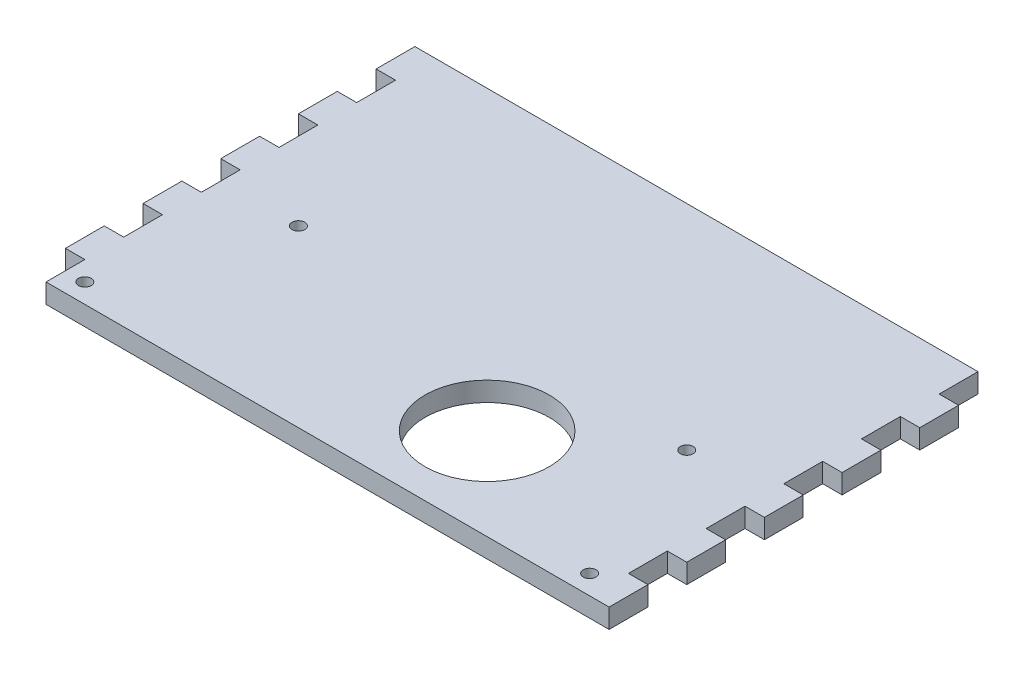
SolidWorks part; units mm, degrees
ref_plane "Front Plane" through (0, 0, 0) normal (0, 0, 1) x (1, 0, 0)
ref_plane "Top Plane" through (0, 0, 0) normal (0, 1, 0) x (1, 0, 0)
ref_plane "Right Plane" through (0, 0, 0) normal (1, 0, 0) x (0, 0, -1)
sketch "Sketch2" plane through (0, 0, 0) normal (0, 1, 0) x (1, 0, 0)
  line L0 (15.875, 0) -> (15.875, 12.7)
  line L2 (15.875, 12.7) -> (9.525, 12.7)
  line L3 (41.275, 57.15) -> (15.875, 57.15) construction
  line L4 (104.775, 0) -> (104.775, 127) construction
  line L5 (9.525, 12.7) -> (9.525, 25.4)
  line L6 (9.525, 25.4) -> (15.875, 25.4)
  line L7 (15.875, 38.1) -> (9.525, 38.1)
  line L8 (9.525, 38.1) -> (9.525, 50.8)
  line L9 (9.525, 50.8) -> (15.875, 50.8)
  line L10 (15.875, 25.4) -> (15.875, 38.1)
  line L11 (15.875, 63.5) -> (9.525, 63.5)
  line L12 (9.525, 63.5) -> (9.525, 76.2)
  line L13 (9.525, 76.2) -> (15.875, 76.2)
  line L14 (15.875, 50.8) -> (15.875, 63.5)
  line L15 (15.875, 88.9) -> (9.525, 88.9)
  line L16 (9.525, 88.9) -> (9.525, 101.6)
  line L17 (9.525, 101.6) -> (15.875, 101.6)
  line L18 (15.875, 76.2) -> (15.875, 88.9)
  line L19 (15.875, 114.3) -> (9.525, 114.3)
  line L20 (9.525, 114.3) -> (9.525, 127)
  line L21 (9.525, 127) -> (15.875, 127)
  line L22 (15.875, 101.6) -> (15.875, 114.3)
  line L25 (200.025, 0) -> (200.025, 12.7)
  line L27 (200.025, 12.7) -> (193.675, 12.7)
  line L28 (193.675, 57.15) -> (168.275, 57.15) construction
  line L29 (193.675, 12.7) -> (193.675, 25.4)
  line L30 (193.675, 25.4) -> (200.025, 25.4)
  line L31 (200.025, 38.1) -> (193.675, 38.1)
  line L32 (193.675, 38.1) -> (193.675, 50.8)
  line L33 (193.675, 50.8) -> (200.025, 50.8)
  line L34 (200.025, 25.4) -> (200.025, 38.1)
  line L35 (15.875, 44.45) -> (15.875, 50.8) construction
  line L36 (15.875, 44.45) -> (130.175, 44.45) construction
  line L37 (130.175, 44.45) -> (130.175, 29.972) construction
  line L38 (200.025, 63.5) -> (193.675, 63.5)
  line L39 (193.675, 63.5) -> (193.675, 76.2)
  line L40 (193.675, 76.2) -> (200.025, 76.2)
  line L41 (200.025, 50.8) -> (200.025, 63.5)
  line L42 (200.025, 88.9) -> (193.675, 88.9)
  line L43 (193.675, 88.9) -> (193.675, 101.6)
  line L44 (193.675, 101.6) -> (200.025, 101.6)
  line L45 (200.025, 76.2) -> (200.025, 88.9)
  line L46 (200.025, 114.3) -> (193.675, 114.3)
  line L47 (193.675, 114.3) -> (193.675, 127)
  line L49 (200.025, 101.6) -> (200.025, 114.3)
  line L53 (15.875, 0) -> (200.025, 0)
  line L54 (200.025, 44.45) -> (200.025, 50.8) construction
  line L55 (15.875, 6.35) -> (22.225, 6.35) construction
  line L56 (193.675, 6.35) -> (187.325, 6.35) construction
  line L57 (15.875, 127) -> (193.675, 127)
  line L77 (9.525, 152.4) -> (15.875, 152.4) [skipped]
  line L78 (9.525, 139.7) -> (9.525, 152.4) [skipped]
  line L79 (15.875, 139.7) -> (9.525, 139.7) [skipped]
  circle A0 centre (41.275, 57.15) radius 2.0828
  circle A1 centre (168.275, 57.15) radius 2.0828
  circle A2 centre (130.175, 29.972) radius 20.32
  circle A3 centre (22.225, 6.35) radius 2.0828
  circle A4 centre (187.325, 6.35) radius 2.0828
  dimension "D1" = 114.3
  dimension "D5" = 25.4
  dimension "D2" = 6
  dimension "D4" = 57.15
  dimension "D8" = 40.64
  dimension "D3" = 29.972
  dimension "D6" = 6.35
  dimension "D7" = 25.4
extrude "Boss-Extrude1" add sketch "Sketch2" along normal blind 6.35
